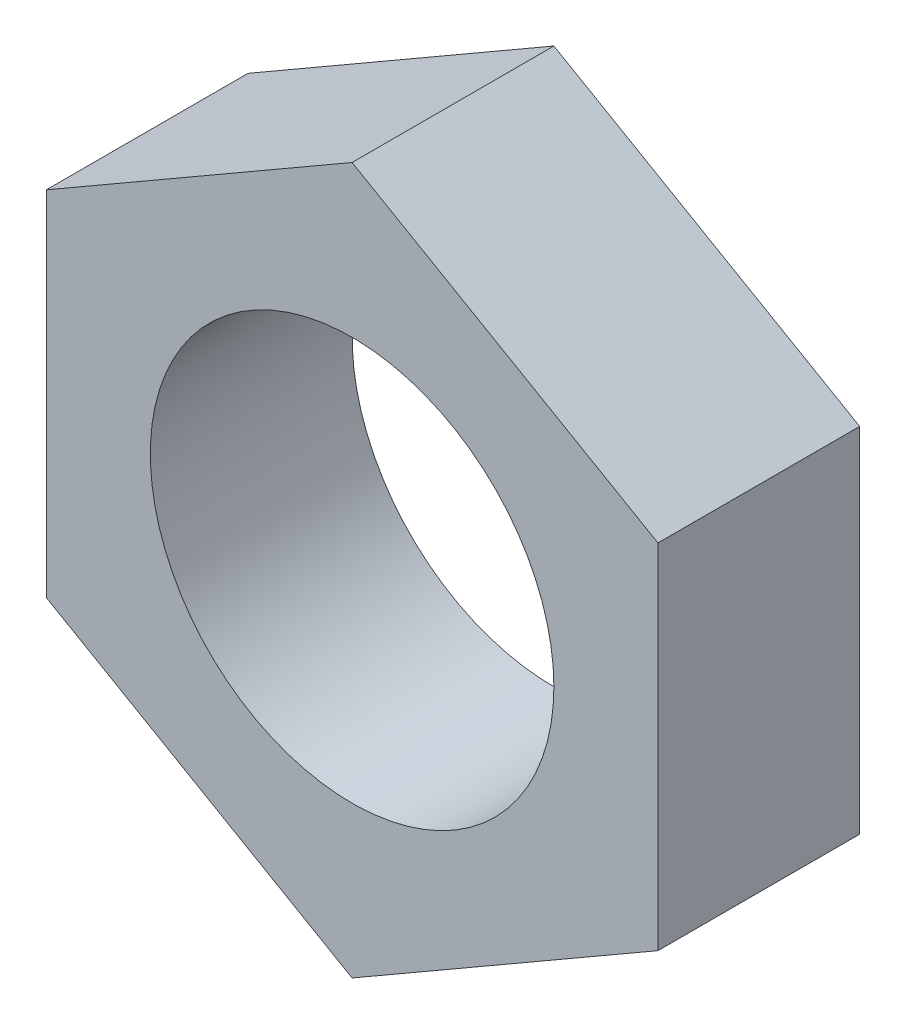
SolidWorks part; units mm, degrees
material "A286, generico"
ref_plane "Piano frontale" through (0, 0, 0) normal (0, 0, 1) x (1, 0, 0)
ref_plane "Piano superiore" through (0, 0, 0) normal (0, 1, 0) x (1, 0, 0)
ref_plane "Piano destro" through (0, 0, 0) normal (1, 0, 0) x (0, 0, -1)
sketch "Schizzo1" plane through (0, 0, 0) normal (0, 0, 1) x (1, 0, 0)
  line L1 (-3.0311, 1.75) -> (-3.0311, -1.75)
  line L2 (-3.0311, -1.75) -> (0, -3.5)
  line L3 (0, -3.5) -> (3.0311, -1.75)
  line L4 (3.0311, -1.75) -> (3.0311, 1.75)
  line L5 (3.0311, 1.75) -> (0, 3.5)
  line L6 (0, 3.5) -> (-3.0311, 1.75)
  circle A0 centre (0, 0) radius 3.0311 construction
  circle A1 centre (0, 0) radius 3.5 construction
  circle A2 centre (0, 0) radius 2
  dimension "D1" = 7
  dimension "D2" = 4
extrude "Estrusione-Estrusione1" add sketch "Schizzo1" along normal blind 2
